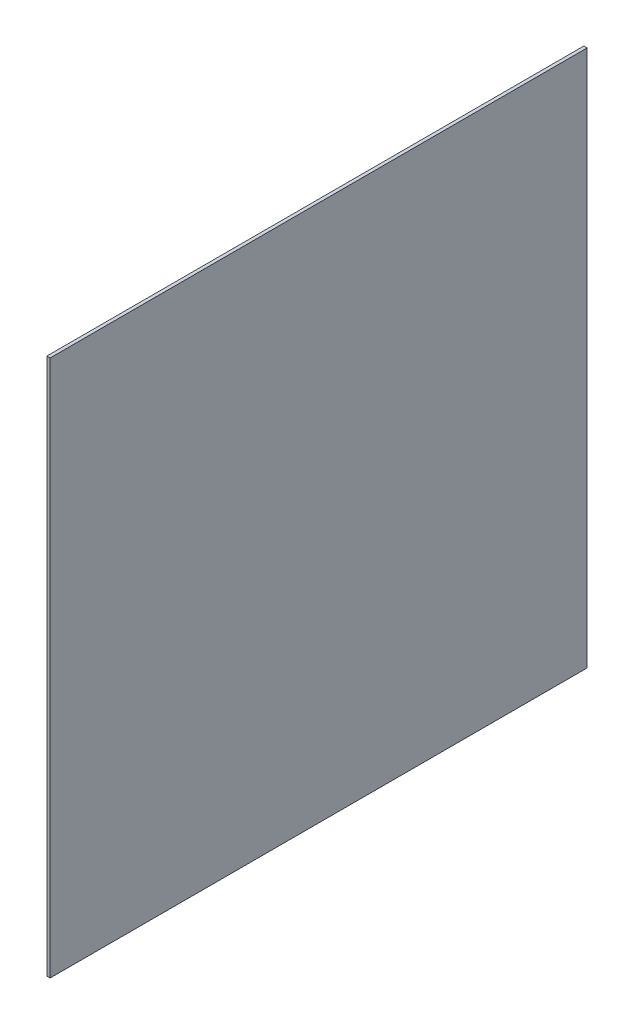
SolidWorks part; units mm, degrees
ref_plane "Front Plane" through (0, 0, 0) normal (0, 0, 1) x (1, 0, 0)
ref_plane "Top Plane" through (0, 0, 0) normal (0, 1, 0) x (1, 0, 0)
ref_plane "Right Plane" through (0, 0, 0) normal (1, 0, 0) x (0, 0, -1)
sketch "Sketch2" plane through (0, 0, 0) normal (1, 0, 0) x (0, 0, -1)
  line L1 (-65.4, 65.4) -> (65.4, 65.4)
  line L2 (-65.4, 65.4) -> (-65.4, -65.4)
  line L3 (-65.4, -65.4) -> (65.4, -65.4)
  line L4 (65.4, 65.4) -> (65.4, -65.4)
  line L5 (-65.4, 65.4) -> (65.4, -65.4) construction
  line L6 (-65.4, -65.4) -> (65.4, 65.4) construction
  point P0 (0, 0)
  dimension "D1" = 130.8
  dimension "D2" = 130.8
extrude "Boss-Extrude1" add sketch "Sketch2" along normal blind 0.8
